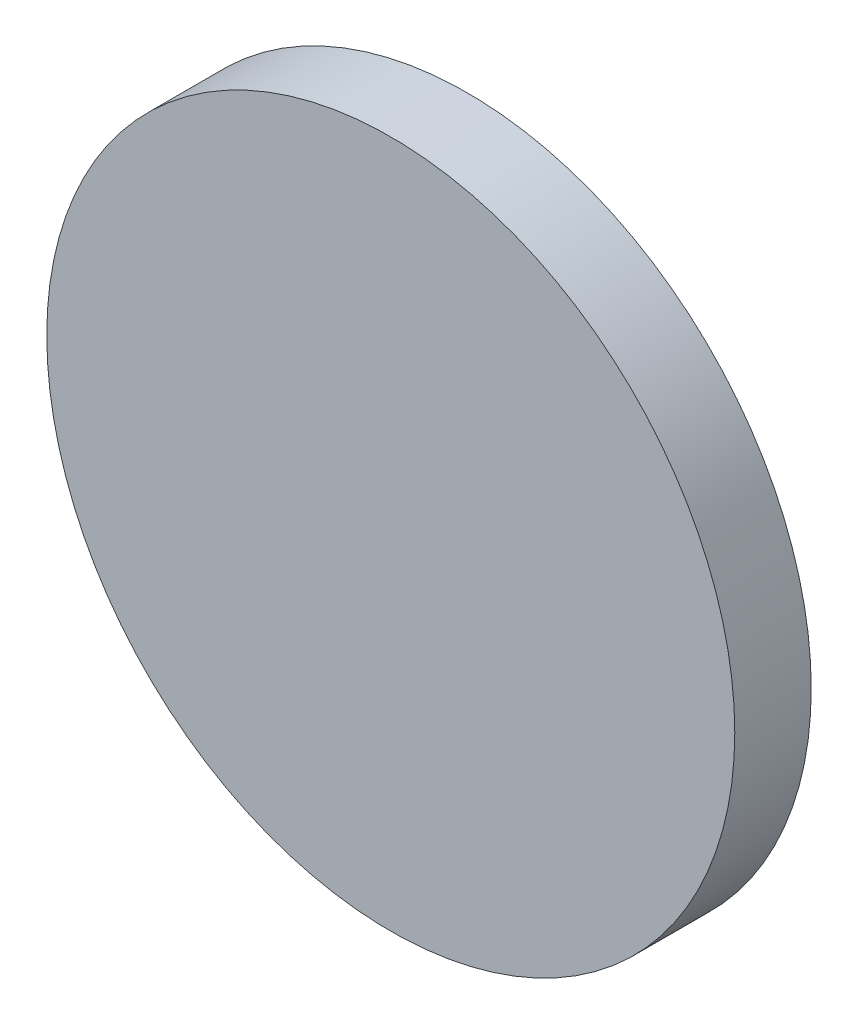
SolidWorks part; units mm, degrees
ref_plane "前视基准面" through (0, 0, 0) normal (0, 0, 1) x (1, 0, 0)
ref_plane "上视基准面" through (0, 0, 0) normal (0, 1, 0) x (1, 0, 0)
ref_plane "右视基准面" through (0, 0, 0) normal (1, 0, 0) x (0, 0, -1)
sketch "草图1" plane through (0, 0, 0) normal (0, 0, 1) x (1, 0, 0)
  circle A0 centre (0, 0) radius 45
  dimension "D1" = 90
extrude "凸台-拉伸1" add sketch "草图1" along normal blind 10
